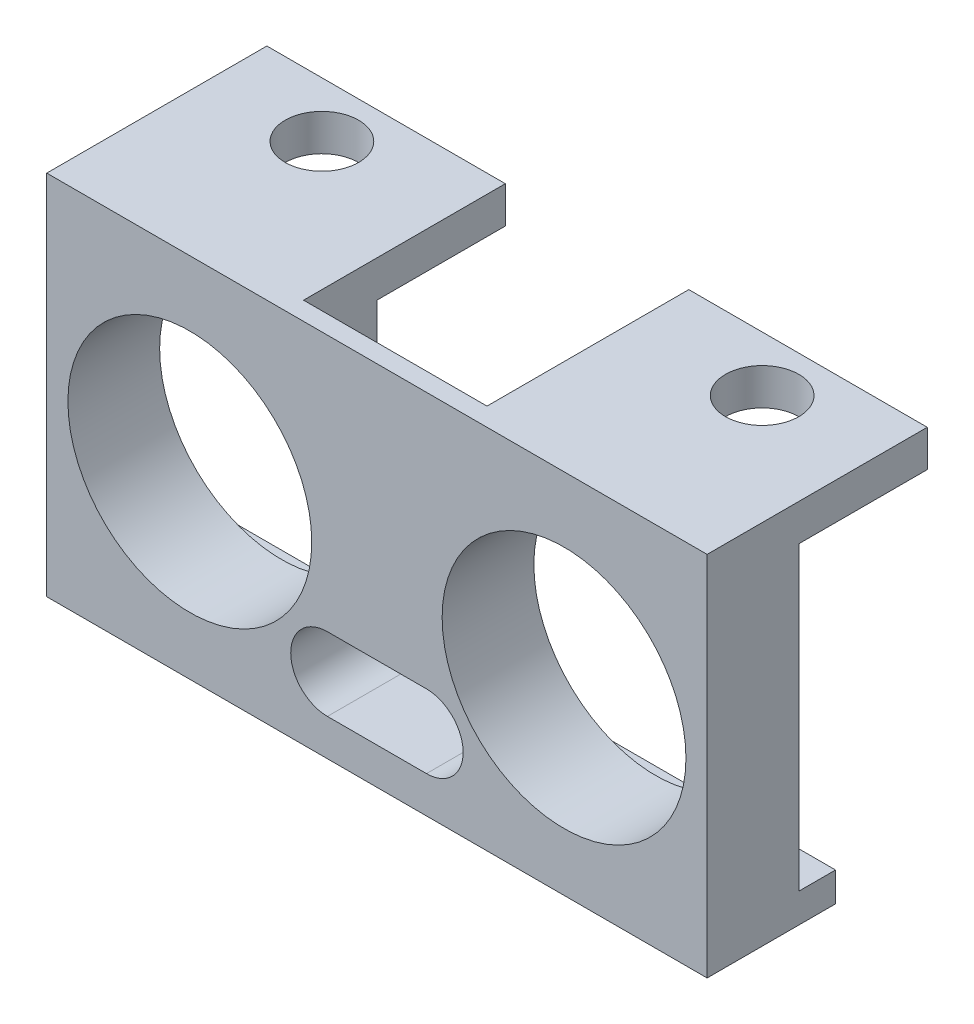
SolidWorks part; units mm, degrees
ref_plane "Front Plane" through (0, 0, 0) normal (0, 0, 1) x (1, 0, 0)
ref_plane "Top Plane" through (0, 0, 0) normal (0, 1, 0) x (1, 0, 0)
ref_plane "Right Plane" through (0, 0, 0) normal (1, 0, 0) x (0, 0, -1)
sketch "Sketch1" plane through (0, 0, 0) normal (0, 0, 1) x (1, 0, 0)
  line L0 (0.239, 22.646) -> (45.489, 22.646) construction
  line L1 (0, 0) -> (45.72, 0)
  line L2 (0, 0) -> (0, 22.86)
  line L3 (0, 22.86) -> (45.72, 22.86)
  line L4 (45.72, 0) -> (45.72, 22.86)
  line L5 (45.489, 2.246) -> (0.239, 2.246) construction
  line L6 (0.239, 2.246) -> (0.239, 22.646) construction
  line L7 (45.489, 22.646) -> (45.489, 2.246) construction
  line L8 (19.431, 5.08) -> (26.289, 5.08) construction
  line L9 (19.431, 7.62) -> (26.289, 7.62)
  line L10 (19.431, 2.54) -> (26.289, 2.54)
  line L11 (26.059, 7.306) -> (19.669, 7.306) construction
  line L12 (19.669, 2.996) -> (26.059, 2.996) construction
  line L13 (19.669, 6.856) -> (19.669, 6.656) construction
  circle A0 centre (9.906, 12.446) radius 8.44
  circle A1 centre (35.814, 12.446) radius 8.44
  circle A4 centre (9.914, 12.446) radius 7.75 construction
  arc A5 (19.431, 7.62) -> (19.431, 2.54) centre (19.431, 5.08) ccw
  arc A6 (26.289, 2.54) -> (26.289, 7.62) centre (26.289, 5.08) ccw
  circle A7 centre (25.703, 5.246) radius 0.25 construction
  point P9 (22.86, 5.08)
  dimension "D1" = 22.86
  dimension "D3" = 16.88
  dimension "D5" = 10.414
  dimension "D6" = 9.675
  dimension "D15" = 17.4
  dimension "D2" = 45.72
  dimension "D4" = 20.4
  dimension "D7" = 9.906
  dimension "D8" = 9.906
  dimension "D9" = 45.25
  dimension "D10" = 4.31
  dimension "D11" = 5.08
  dimension "D12" = 6.39
  dimension "D13" = 6.858
  dimension "D14" = 22.86
  dimension "D16" = 17.78
extrude "Boss-Extrude1" add sketch "Sketch1" along normal blind 6.35
sketch "Sketch2" plane through (0, 0, 0) normal (0, 0, -1) x (-1, 0, 0)
  line L0 (-45.72, 22.86) -> (0, 22.86) construction
  line L1 (-29.21, 22.86) -> (-16.51, 22.86)
  line L2 (-29.21, 22.86) -> (-29.21, 19.05)
  line L3 (-29.21, 19.05) -> (-16.51, 19.05)
  line L4 (-16.51, 22.86) -> (-16.51, 19.05)
  point P7 (-22.86, 22.86)
  point P8 (-22.86, 22.86)
  dimension "D1" = 12.7
  dimension "D2" = 3.81
  dimension "D3" = 0
extrude "Cut-Extrude1" cut sketch "Sketch2" against normal blind 5.08
sketch "Sketch3" plane through (0, 22.86, 0) normal (0, 1, 0) x (1, 0, 0)
  line L0 (0, -6.35) -> (0, 8.89)
  line L1 (0, 8.89) -> (16.51, 8.89)
  line L2 (16.51, 8.89) -> (16.51, -5.08)
  line L3 (16.51, -5.08) -> (29.21, -5.08)
  line L4 (29.21, -5.08) -> (29.21, 8.89)
  line L5 (29.21, 8.89) -> (45.72, 8.89)
  line L6 (45.72, 8.89) -> (45.72, -6.35)
  line L7 (45.72, -6.35) -> (0, -6.35)
  dimension "D1" = 15.24
extrude "Boss-Extrude2" add sketch "Sketch3" along normal blind 2.54 contours L1 L2 L3 L4 L5 L6 L7 L0
sketch "Sketch4" plane through (0, 0, 0) normal (0, 0, -1) x (-1, 0, 0)
  line L0 (0, 22.86) -> (0, 0) construction
  line L1 (-45.72, 0) -> (0, 0)
  line L2 (-45.72, 0) -> (-45.72, 2.032)
  line L3 (-45.72, 2.032) -> (0, 2.032)
  line L4 (0, 0) -> (0, 2.032)
  dimension "D1" = 2.032
extrude "Boss-Extrude3" add sketch "Sketch4" along normal blind 2.54
sketch "Sketch5" plane through (0, 22.86, 0) normal (0, -1, 0) x (1, 0, 0)
  line L0 (22.86, 6.35) -> (22.86, -2.54) construction
  line L1 (0, 6.35) -> (45.72, 6.35) construction
  line L2 (45.72, -2.54) -> (0, -2.54) construction
  circle A0 centre (38.1, -5.08) radius 2.54
  circle A1 centre (7.62, -5.08) radius 2.54
  dimension "D1" = 5.08
  dimension "D2" = 15.24
  dimension "D3" = 11.43
extrude "Cut-Extrude2" cut sketch "Sketch5" against normal through all
